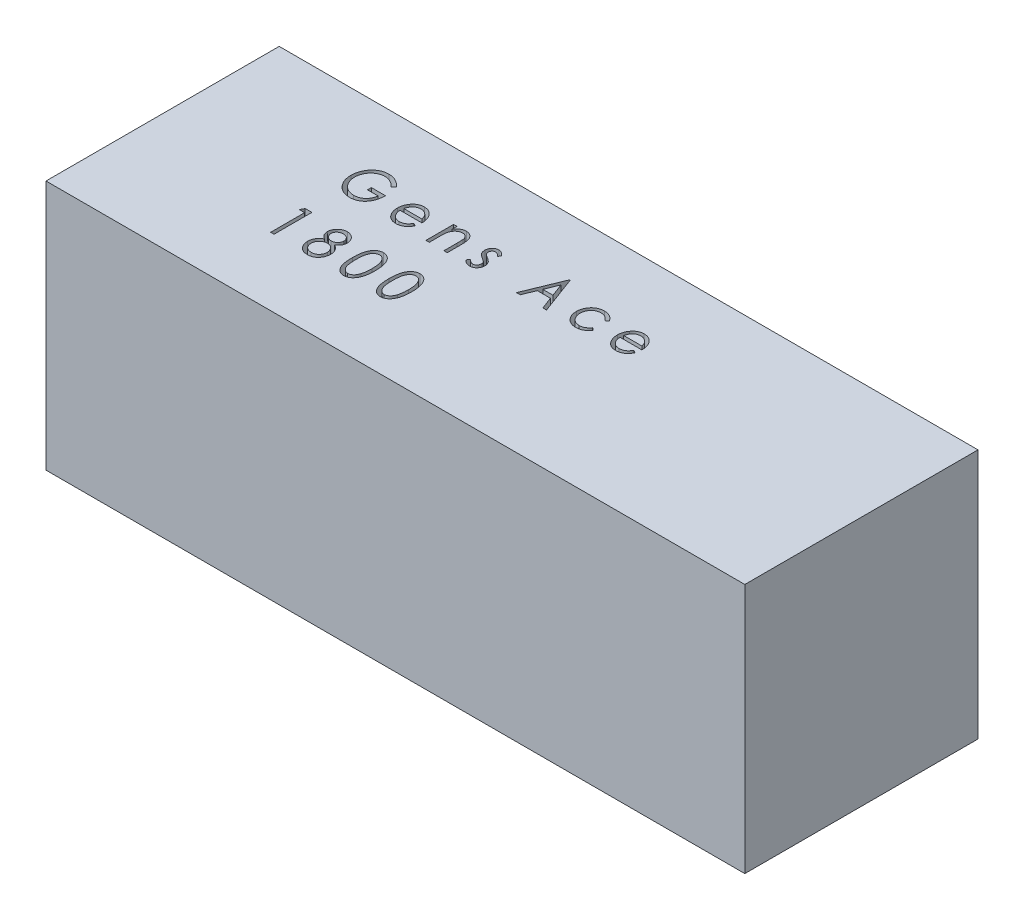
SolidWorks part; units mm, degrees
ref_plane "Front Plane" through (0, 0, 0) normal (0, 0, 1) x (1, 0, 0)
ref_plane "Top Plane" through (0, 0, 0) normal (0, 1, 0) x (1, 0, 0)
ref_plane "Right Plane" through (0, 0, 0) normal (1, 0, 0) x (0, 0, -1)
sketch "Sketch1" plane through (0, 0, 0) normal (0, 1, 0) x (1, 0, 0)
  line L1 (-46.155, 15.4) -> (46.155, 15.4)
  line L2 (-46.155, 15.4) -> (-46.155, -15.4)
  line L3 (-46.155, -15.4) -> (46.155, -15.4)
  line L4 (46.155, 15.4) -> (46.155, -15.4)
  line L5 (-46.155, 15.4) -> (46.155, -15.4) construction
  line L6 (-46.155, -15.4) -> (46.155, 15.4) construction
  point P0 (0, 0)
  dimension "D1" = 92.31
  dimension "D2" = 30.8
extrude "Boss-Extrude1" add sketch "Sketch1" along normal blind 33.08
sketch "Sketch2" plane through (0, 33.08, 0) normal (0, 1, 0) x (1, 0, 0)
  text T0 "Gens Ace \r\n1800" font "Century Gothic" height 5
extrude "Cut-Extrude1" cut sketch "Sketch2" against normal blind 15
sketch3d "3DSketch1"
  line L0 (46.155, 33.08, 15.4) -> (-46.155, 0, -15.4) construction
  line L1 (46.155, 33.08, 15.4) -> (46.155, 33.08, -15.4) construction
  line L2 (46.155, 0, -15.4) -> (-46.155, 0, -15.4) construction
  line L3 (-46.155, 33.08, -15.4) -> (-46.155, 0, -15.4) construction
  line L4 (-46.155, 33.08, 15.4) -> (46.155, 0, -15.4) construction
  line L5 (-46.155, 33.08, -15.4) -> (-46.155, 33.08, 15.4) construction
  line L6 (-46.155, 33.08, 15.4) -> (46.155, 33.08, 15.4) construction
  line L7 (46.155, 33.08, -15.4) -> (46.155, 0, -15.4) construction
  point P16 (0, 16.54, 0)
